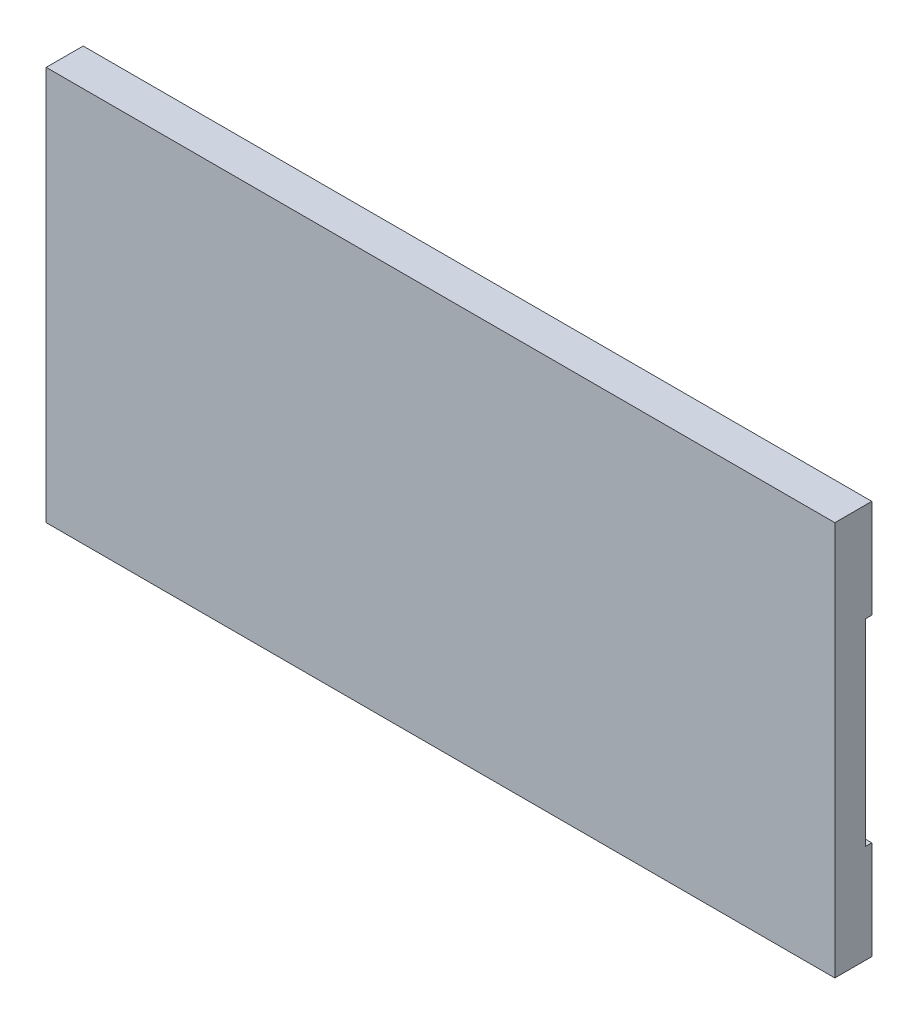
SolidWorks part; units mm, degrees
ref_plane "Front" through (0, 0, 0) normal (0, 0, 1) x (1, 0, 0)
ref_plane "Top" through (0, 0, 0) normal (0, 1, 0) x (1, 0, 0)
ref_plane "Right" through (0, 0, 0) normal (1, 0, 0) x (0, 0, -1)
sketch "Sketch1" plane through (0, 0, 0) normal (0, 0, 1) x (1, 0, 0)
  line L1 (0, 0) -> (203.2, 0)
  line L2 (0, 0) -> (0, 101.6)
  line L3 (0, 101.6) -> (203.2, 101.6)
  line L4 (203.2, 0) -> (203.2, 101.6)
  dimension "D1" = 101.6
  dimension "D2" = 203.2
extrude "Boss-Extrude1" add sketch "Sketch1" along normal blind 9.525
sketch "Sketch2" plane through (0, 0, 0) normal (1, 0, 0) x (0, 0, -1)
  line L0 (0, 0) -> (0, 101.6) construction
  line L1 (0, 76.2) -> (-1.5875, 76.2)
  line L2 (0, 76.2) -> (0, 25.4)
  line L3 (0, 25.4) -> (-1.5875, 25.4)
  line L4 (-1.5875, 76.2) -> (-1.5875, 25.4)
  line L5 (-9.525, 101.6) -> (0, 101.6) construction
  dimension "D1" = 25.4
  dimension "D2" = 50.8
  dimension "D3" = 1.5875
extrude "Cut-Extrude1" cut sketch "Sketch2" against normal through all and the other way through all from offset 60.325
